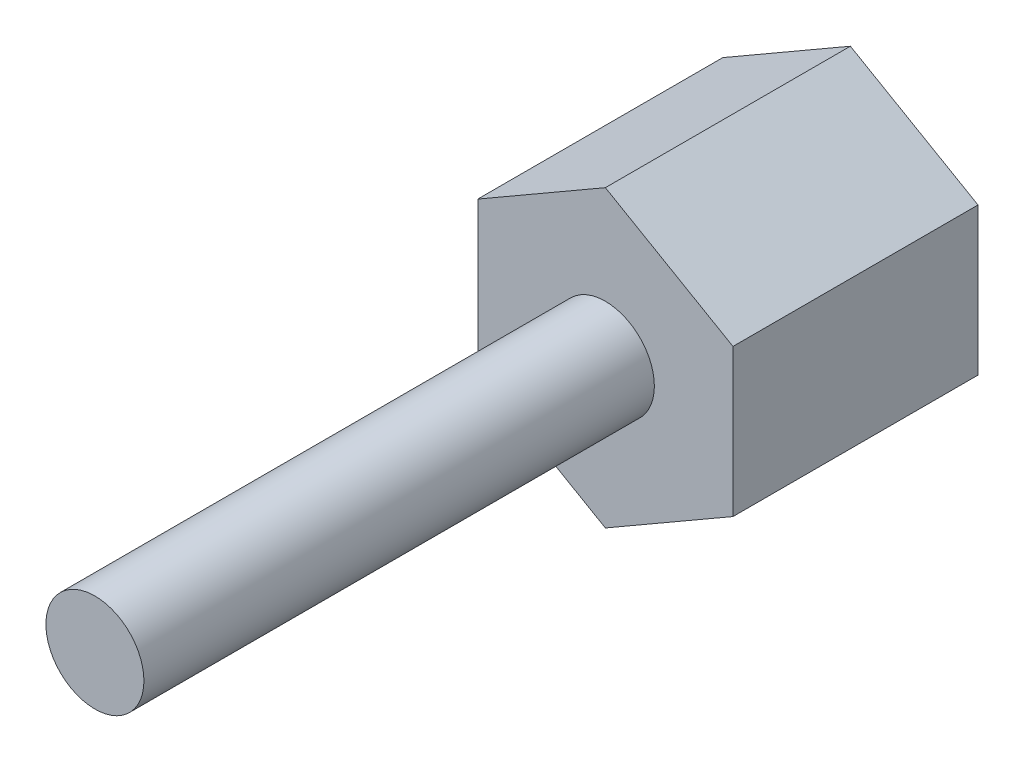
SolidWorks part; units mm, degrees
ref_plane "Alzado" through (0, 0, 0) normal (0, 0, 1) x (1, 0, 0)
ref_plane "Planta" through (0, 0, 0) normal (0, 1, 0) x (1, 0, 0)
ref_plane "Vista lateral" through (0, 0, 0) normal (1, 0, 0) x (0, 0, -1)
sketch "Croquis1" plane through (0, 0, 0) normal (0, 0, 1) x (1, 0, 0)
  line L0 (0, 0) -> (0, 7.2169) construction
  line L2 (0, 7.2169) -> (-6.25, 3.6084)
  line L3 (-6.25, 3.6084) -> (-6.25, -3.6084)
  line L4 (-6.25, -3.6084) -> (0, -7.2169)
  line L5 (0, -7.2169) -> (6.25, -3.6084)
  line L6 (6.25, -3.6084) -> (6.25, 3.6084)
  line L7 (6.25, 3.6084) -> (0, 7.2169)
  circle A0 centre (0, 0) radius 6.25 construction
  dimension "D1" = 12.5
extrude "Saliente-Extruir1" add sketch "Croquis1" along normal blind 12
sketch "Croquis2" plane through (0, 0, 12) normal (0, 0, 1) x (1, 0, 0)
  circle A0 centre (0, 0) radius 2.4
  dimension "D1" = 4.8
extrude "Saliente-Extruir2" add sketch "Croquis2" along normal blind 25
